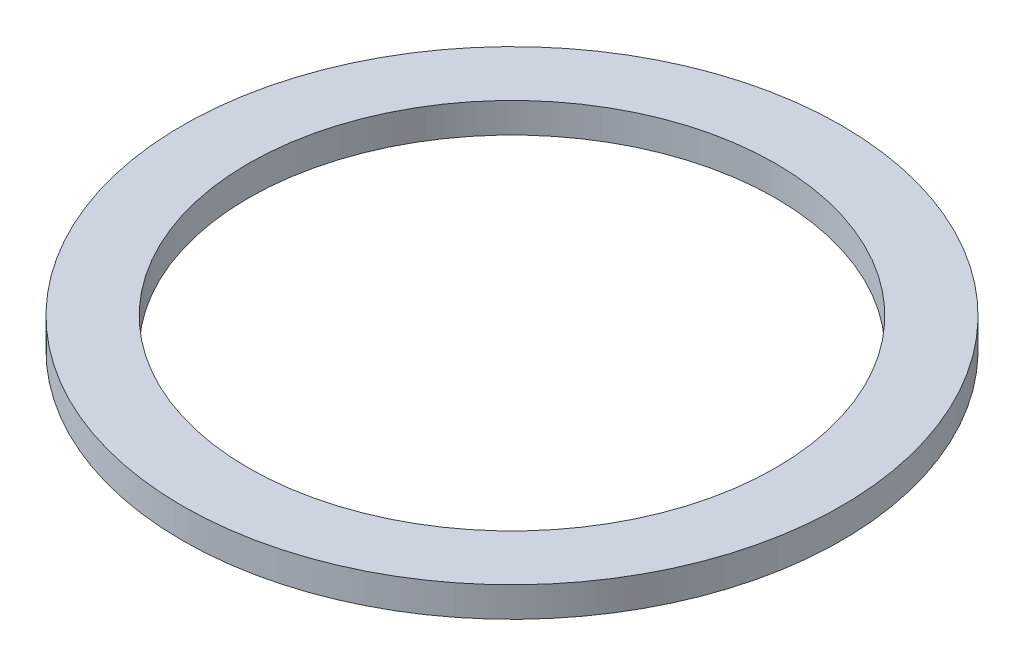
SolidWorks part; units mm, degrees
ref_plane "Front Plane" through (0, 0, 0) normal (0, 0, 1) x (1, 0, 0)
ref_plane "Top Plane" through (0, 0, 0) normal (0, 1, 0) x (1, 0, 0)
ref_plane "Right Plane" through (0, 0, 0) normal (1, 0, 0) x (0, 0, -1)
sketch "Sketch1" plane through (0, 0, 0) normal (1, 0, 0) x (0, 0, -1)
  line L0 (0, 166.7755) -> (0, -146.671) construction
  line L1 (0, 0) -> (-418.5379, 0) construction
  line L2 (-275, 12.5) -> (-275, -12.5)
  line L3 (-275, -12.5) -> (-220, -12.5)
  line L4 (-220, -12.5) -> (-220, 12.5)
  line L5 (-220, 12.5) -> (-275, 12.5)
  point P7 (-220, 0)
  dimension "D1" = 550
  dimension "D2" = 440
  dimension "D3" = 25
revolve "Revolve1" add sketch "Sketch1" angle 360 about L0
